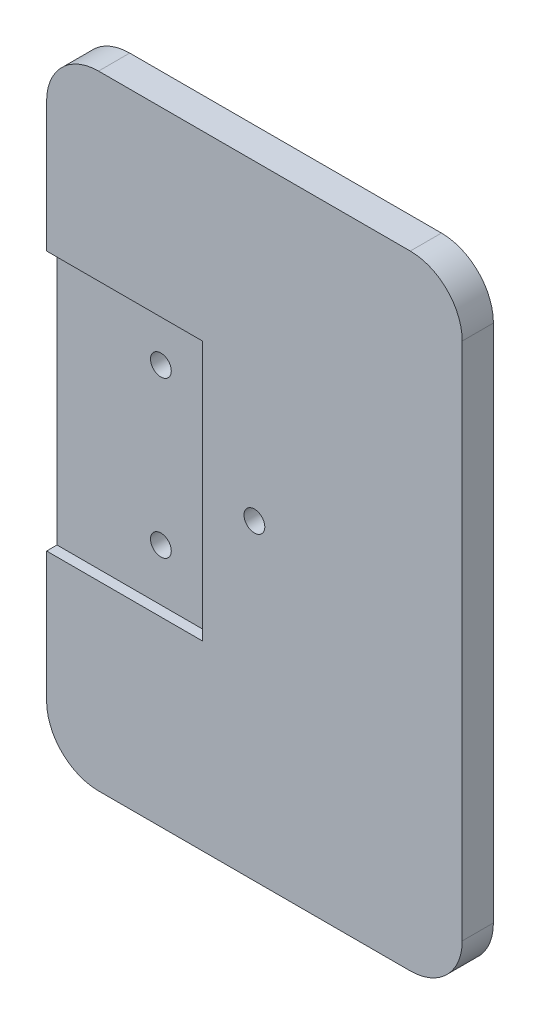
SolidWorks part; units mm, degrees
ref_plane "Front Plane" through (0, 0, 0) normal (0, 0, 1) x (1, 0, 0)
ref_plane "Top Plane" through (0, 0, 0) normal (0, 1, 0) x (1, 0, 0)
ref_plane "Right Plane" through (0, 0, 0) normal (1, 0, 0) x (0, 0, -1)
sketch "Sketch1" plane through (0, 0, 0) normal (0, 0, 1) x (1, 0, 0)
  line L1 (-65.9851, 26.8064) -> (-25.9851, 26.8064)
  line L2 (-65.9851, 26.8064) -> (-65.9851, -33.1936)
  line L3 (-65.9851, -33.1936) -> (-25.9851, -33.1936)
  line L4 (-25.9851, 26.8064) -> (-25.9851, -33.1936)
  dimension "D1" = 40
  dimension "D2" = 60
extrude "Boss-Extrude4" add sketch "Sketch1" against normal blind 3 contours L2 L3 L4 L1
sketch "Sketch5" plane through (0, 0, 0) normal (0, 0, 1) x (1, 0, 0)
  line L0 (-65.9851, 26.8064) -> (-65.9851, -33.1936) construction
  line L1 (-65.9851, 9.3064) -> (-50.9851, 9.3064)
  line L2 (-65.9851, 9.3064) -> (-65.9851, -15.6936)
  line L3 (-65.9851, -15.6936) -> (-50.9851, -15.6936)
  line L4 (-50.9851, 9.3064) -> (-50.9851, -15.6936)
  line L5 (-65.9851, 26.8064) -> (-25.9851, 26.8064) construction
  dimension "D1" = 15
  dimension "D2" = 25
  dimension "D3" = 17.5
extrude "Cut-Extrude2" cut sketch "Sketch5" against normal blind 1 contours L2 L1 L4 L3
sketch "Sketch7" plane through (0, 0, -1) normal (0, 0, 1) x (1, 0, 0)
  line L0 (-65.9851, 9.3064) -> (-50.9851, 9.3064) construction
  line L1 (-50.9851, 9.3064) -> (-50.9851, -15.6936) construction
  circle A0 centre (-55.9851, 4.3064) radius 1
  dimension "D1" = 2
  dimension "D2" = 5
  dimension "D3" = 5
extrude "Cut-Extrude3" cut sketch "Sketch7" against normal blind 2
sketch "Sketch8" plane through (0, 0, -1) normal (0, 0, 1) x (1, 0, 0)
  line L0 (-50.9851, 9.3064) -> (-50.9851, -15.6936) construction
  line L1 (-65.9851, -15.6936) -> (-50.9851, -15.6936) construction
  circle A0 centre (-55.9851, -10.6936) radius 1
  dimension "D1" = 5
  dimension "D3" = 2
  dimension "D2" = 5
extrude "Cut-Extrude4" cut sketch "Sketch8" against normal blind 2
fillet "Fillet1" radius 5 4 edges at (-25.9851, 26.8064, -1.5) (-25.9851, -33.1936, -1.5) (-65.9851, -33.1936, -1.5) (-65.9851, 26.8064, -1.5)
sketch "Sketch12" plane through (0, 0, -3) normal (0, 0, -1) x (-1, 0, 0)
  line L0 (65.9851, 21.8064) -> (65.9851, -28.1936) construction
  line L1 (60.9851, 26.8064) -> (30.9851, 26.8064) construction
  circle A0 centre (45.9851, -3.1936) radius 1
  dimension "D1" = 2
  dimension "D2" = 20
  dimension "D3" = 30
extrude "Cut-Extrude6" cut sketch "Sketch12" against normal blind 12 contours A0
